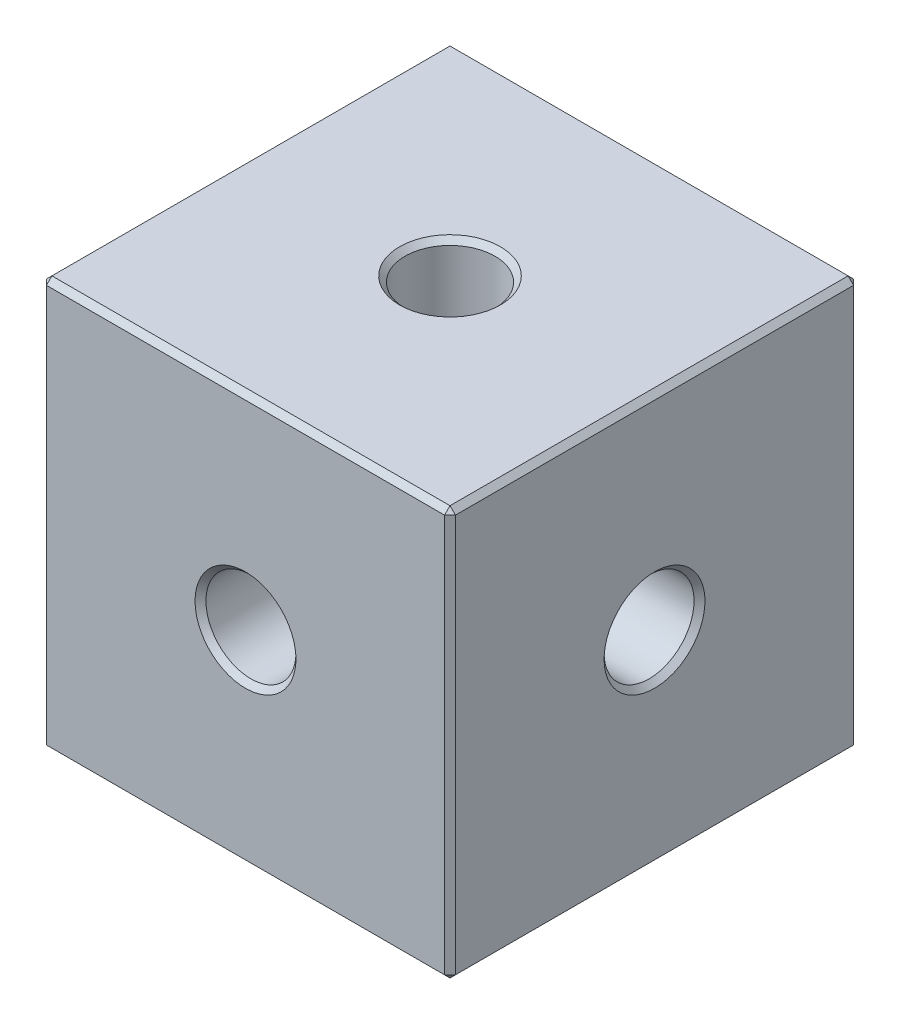
SolidWorks part; units mm, degrees
ref_plane "前视基准面" through (0, 0, 0) normal (0, 0, 1) x (1, 0, 0)
ref_plane "上视基准面" through (0, 0, 0) normal (0, 1, 0) x (1, 0, 0)
ref_plane "右视基准面" through (0, 0, 0) normal (1, 0, 0) x (0, 0, -1)
sketch "草图1" plane through (0, 0, 0) normal (0, 1, 0) x (1, 0, 0)
  line L1 (-7.5, 7.5) -> (7.5, 7.5)
  line L2 (-7.5, 7.5) -> (-7.5, -7.5)
  line L3 (-7.5, -7.5) -> (7.5, -7.5)
  line L4 (7.5, 7.5) -> (7.5, -7.5)
  line L5 (-7.5, 7.5) -> (7.5, -7.5) construction
  line L6 (-7.5, -7.5) -> (7.5, 7.5) construction
  point P0 (0, 0)
  dimension "D1" = 15
extrude "凸台-拉伸1" add sketch "草图1" along normal mid plane 15
hole_wizard "M4 螺纹孔1" positions "草图2" profile "草图3" tap size "M4" standard "GB" end condition through all
sketch "草图2" plane through (0, 0, 7.5) normal (0, 0, 1) x (1, 0, 0)
  point P0 (0, 0)
sketch "草图3" plane through (0, 0, 7.5) normal (1, 0, 0) x (0, -1, 0)
  line L0 (0, 0) -> (0, 15)
  line L1 (0, 15) -> (1.65, 15)
  line L2 (1.65, 15) -> (1.65, 0)
  line L5 (1.65, 0) -> (0, 0)
  line L11 (0, -6.35) -> (0, 107.95) construction
  dimension "通孔螺纹孔钻头直径" = 3.3
  dimension "通孔螺纹孔钻头深度" = 15
cosmetic thread "孔螺蚊线1"
hole_wizard "M4 螺纹孔2" positions "草图4" profile "草图5" tap size "M4" standard "GB" end condition through all
sketch "草图4" plane through (0, 7.5, 0) normal (0, 1, 0) x (1, 0, 0)
  point P0 (0, 0)
sketch "草图5" plane through (0, 7.5, 0) normal (1, 0, 0) x (0, 0, 1)
  line L0 (0, 0) -> (0, 15)
  line L1 (0, 15) -> (1.65, 15)
  line L2 (1.65, 15) -> (1.65, 0)
  line L5 (1.65, 0) -> (0, 0)
  line L11 (0, -6.35) -> (0, 107.95) construction
  dimension "通孔螺纹孔钻头直径" = 3.3
  dimension "通孔螺纹孔钻头深度" = 15
cosmetic thread "孔螺蚊线2" parameters "D2"=4
hole_wizard "M4 螺纹孔3" positions "草图6" profile "草图7" tap size "M4" standard "GB" end condition through all
sketch "草图6" plane through (7.5, 0, 0) normal (1, 0, 0) x (0, 0, -1)
  point P0 (0, 0)
sketch "草图7" plane through (7.5, 0, 0) normal (0, 1, 0) x (0, 0, -1)
  line L0 (0, 0) -> (0, 15)
  line L1 (0, 15) -> (1.65, 15)
  line L2 (1.65, 15) -> (1.65, 0)
  line L5 (1.65, 0) -> (0, 0)
  line L11 (0, -6.35) -> (0, 107.95) construction
  dimension "通孔螺纹孔钻头直径" = 3.3
  dimension "通孔螺纹孔钻头深度" = 15
cosmetic thread "孔螺蚊线3"
chamfer "倒角1" distance 0.2 angle 45 18 edges at (0, -7.5, 1.65) (-7.5, 0, -1.65) (1.65, 0, -7.5) (7.5, 0, -1.65) (1.65, 0, 7.5) (-7.5, -7.5, 0) (-7.5, 0, -7.5) (0, -7.5, -7.5) (7.5, 0, -7.5) (7.5, -7.5, 0) (-7.5, 0, 7.5) (0, -7.5, 7.5) (7.5, 0, 7.5) (0, 7.5, 7.5) (-7.5, 7.5, 0) (0, 7.5, -7.5) (7.5, 7.5, 0) (0, 7.5, 1.65)
